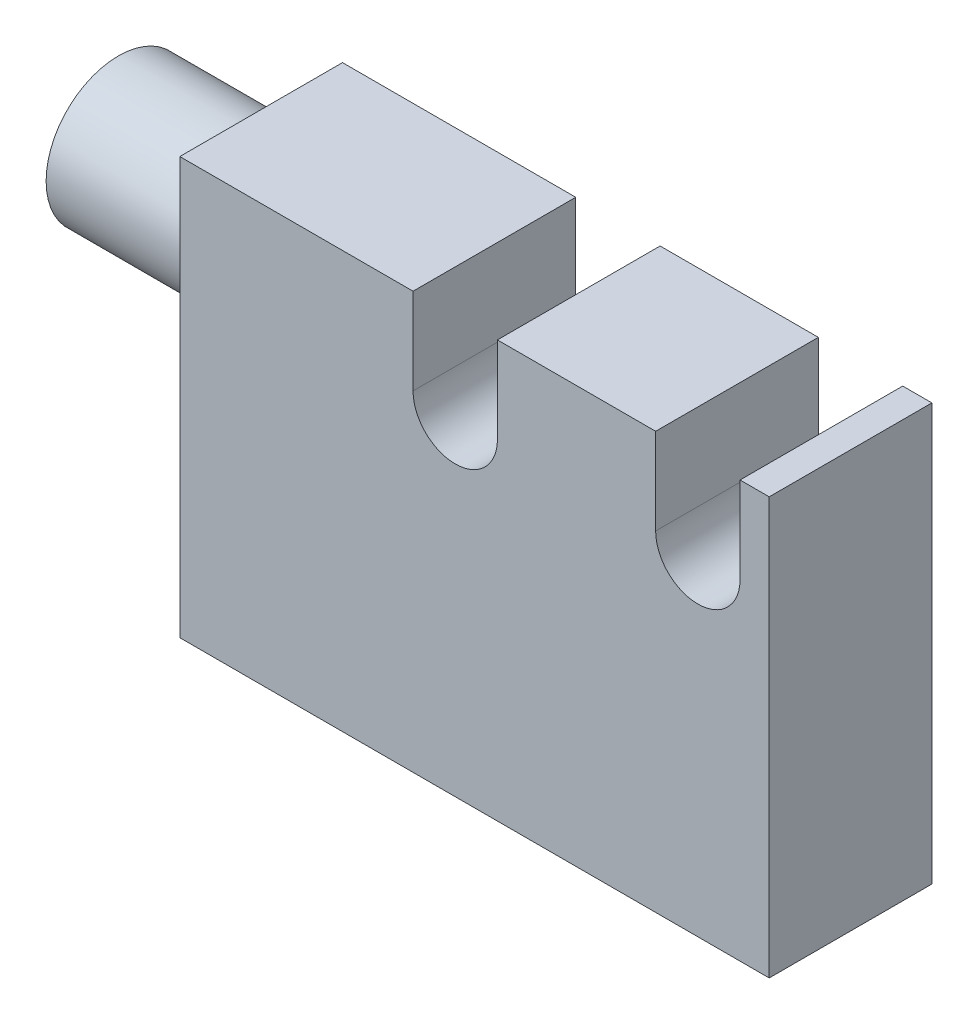
SolidWorks part; units mm, degrees
ref_plane "Front Plane" through (0, 0, 0) normal (0, 0, 1) x (1, 0, 0)
ref_plane "Top Plane" through (0, 0, 0) normal (0, 1, 0) x (1, 0, 0)
ref_plane "Right Plane" through (0, 0, 0) normal (1, 0, 0) x (0, 0, -1)
sketch "Sketch1" plane through (0, 0, 0) normal (0, 0, 1) x (1, 0, 0)
  line L0 (0, 0) -> (-41.3, 0)
  line L1 (-41.3, 0) -> (-41.3, 13)
  line L2 (-41.3, 13) -> (-24.956, 13)
  line L3 (-24.956, 13) -> (-24.956, 6.95)
  line L4 (-19.044, 6.95) -> (-19.044, 13)
  line L5 (-19.044, 13) -> (-7.956, 13)
  line L6 (-7.956, 13) -> (-7.956, 6.95)
  line L7 (-2.044, 6.95) -> (-2.044, 13)
  line L8 (-2.044, 13) -> (0, 13)
  line L9 (0, 13) -> (0, 0)
  arc A0 (-24.956, 6.95) -> (-19.044, 6.95) centre (-22, 6.95) ccw
  arc A1 (-7.956, 6.95) -> (-2.044, 6.95) centre (-5, 6.95) ccw
  dimension "D1" = 41.3
  dimension "D2" = 17
  dimension "D3" = 5
  dimension "D4" = 6.05
  dimension "D5" = 6.05
  dimension "D6" = 6.05
  dimension "D7" = 6.05
  dimension "D8" = 13
extrude "Boss-Extrude1" add sketch "Sketch1" along normal blind 11.4
sketch "Sketch2" plane through (0, 0, 0) normal (0, -1, 0) x (1, 0, 0)
  line L4 (-41.3, 0) -> (0, 0)
  line L5 (0, 0) -> (0, 11.4)
  line L6 (0, 11.4) -> (-41.3, 11.4)
  line L7 (-41.3, 11.4) -> (-41.3, 0)
  line L8 (-41.3, 0) -> (0, 0)
  line L9 (0, 0) -> (0, 11.4)
  line L10 (0, 11.4) -> (-41.3, 11.4)
  line L11 (-41.3, 11.4) -> (-41.3, 0)
  dimension "D1" = 0
extrude "Boss-Extrude2" add sketch "Sketch2" along normal blind 16.2
sketch "Sketch3" plane through (-41.3, 0, 0) normal (-1, 0, 0) x (0, 0, 1)
  line L0 (11.4, 13) -> (0, 13) construction
  circle A0 centre (5.7, 6.1921) radius 5.0682
  point P4 (5.7, 13)
extrude "Boss-Extrude3" add sketch "Sketch3" along normal blind 10 contours A0
sketch "Sketch6" plane through (0, 0, 0) normal (0, 0, -1) x (-1, 0, 0)
  line L1 (-4.2913, -6.8223) -> (33.7087, -6.8223)
  line L2 (33.7087, 33.1777) -> (-4.2913, 33.1777)
  line L5 (2.044, 19.05) -> (2.044, 13)
  line L6 (7.956, 19.05) -> (7.956, 13)
  line L7 (19.044, 19.05) -> (19.044, 13)
  line L8 (24.956, 19.05) -> (24.956, 13)
  line L10 (0, 13) -> (0, -16.2)
  line L11 (0, -16.2) -> (41.3, -16.2)
  line L12 (41.3, -16.2) -> (41.3, 13)
  line L13 (41.3, 13) -> (24.956, 13)
  line L14 (24.956, 13) -> (24.956, 6.95)
  line L15 (19.044, 6.95) -> (19.044, 13)
  line L16 (19.044, 13) -> (7.956, 13)
  line L17 (7.956, 13) -> (7.956, 6.95)
  line L18 (2.044, 6.95) -> (2.044, 13)
  line L19 (2.044, 13) -> (0, 13)
  line L20 (-4.2913, 33.1777) -> (-4.2913, -6.8223)
  line L22 (33.7087, -6.8223) -> (33.7087, 33.1777)
  line L24 (24.956, 13) -> (24.956, 6.95)
  line L25 (19.044, 6.95) -> (19.044, 13)
  line L27 (7.956, 13) -> (7.956, 6.95)
  line L28 (2.044, 6.95) -> (2.044, 13)
  arc A0 (19.044, 19.05) -> (24.956, 19.05) centre (22, 19.05) cw
  arc A1 (2.044, 19.05) -> (7.956, 19.05) centre (5, 19.05) cw
  arc A2 (19.044, 6.95) -> (24.956, 6.95) centre (22, 6.95) ccw
  arc A3 (2.044, 6.95) -> (7.956, 6.95) centre (5, 6.95) ccw
  arc A4 (19.044, 6.95) -> (24.956, 6.95) centre (22, 6.95) ccw
  arc A5 (2.044, 6.95) -> (7.956, 6.95) centre (5, 6.95) ccw
  dimension "D2" = 38
  dimension "D3" = 40
  dimension "D1" = 0
